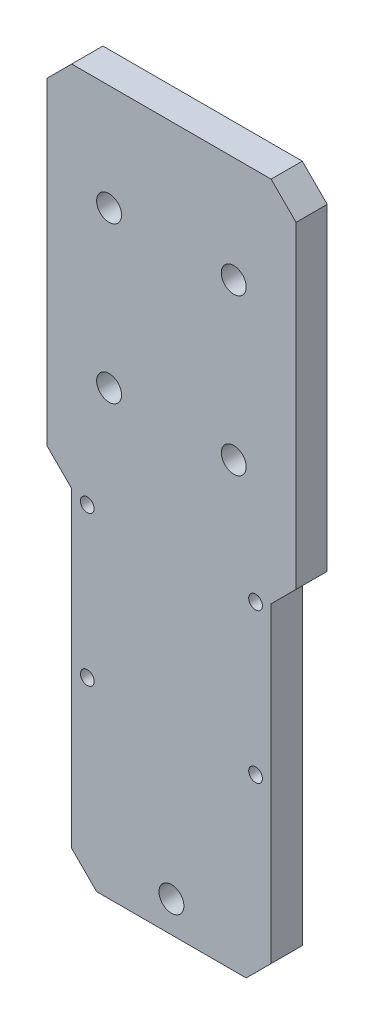
SolidWorks part; units mm, degrees
ref_plane "Alzado" through (0, 0, 0) normal (0, 0, 1) x (1, 0, 0)
ref_plane "Planta" through (0, 0, 0) normal (0, 1, 0) x (1, 0, 0)
ref_plane "Vista lateral" through (0, 0, 0) normal (1, 0, 0) x (0, 0, -1)
sketch "Croquis1" plane through (0, 0, 0) normal (0, 0, 1) x (1, 0, 0)
  line L0 (0, -27.5) -> (0, -61.5) construction
  line L1 (-20, 27.5) -> (20, 27.5)
  line L2 (-20, 27.5) -> (-20, -27.5)
  line L3 (-20, -27.5) -> (20, -27.5)
  line L4 (20, 27.5) -> (20, -27.5)
  line L5 (-20, 27.5) -> (20, -27.5) construction
  line L6 (-20, -27.5) -> (20, 27.5) construction
  line L7 (0, -32.5) -> (-13.5, -32.5) construction
  line L8 (16, -61.5) -> (-16, -61.5)
  line L9 (0, -61.5) -> (0, -27.5)
  line L10 (16, -27.5) -> (-16, -27.5)
  line L11 (-16, -61.5) -> (-16, -27.5)
  line L12 (-20, -27.5) -> (-16, -31.5)
  line L13 (20, -27.5) -> (16, -31.5)
  line L14 (16, -61.5) -> (16, -27.5)
  circle A0 centre (-13.5, -32.5) radius 1.1
  circle A3 centre (-13.5, -56.5) radius 1.1
  circle A4 centre (13.5, -32.5) radius 1.1
  circle A7 centre (13.5, -56.5) radius 1.1
  circle A8 centre (-13.5, -40.5) radius 1.1 [skipped]
  circle A9 centre (-13.5, -48.5) radius 1.1 [skipped]
  point P0 (0, 0)
  dimension "D5" = 2.2
  dimension "D1" = 40
  dimension "D2" = 55
  dimension "D3" = 16
  dimension "D4" = 13.5
  dimension "D7" = 34
  dimension "D8" = 5
  dimension "D9" = 45
  dimension "D6" = 4
extrude "FormaBase" add sketch "Croquis1" along normal blind 5
sketch "Croquis2" plane through (0, 0, 5) normal (0, 0, 1) x (1, 0, 0)
  line L0 (-20, 27.5) -> (-20, 23.4978)
  line L1 (-20, 27.5) -> (-20, -27.5) construction
  line L2 (-20, 23.4978) -> (-15.9978, 27.5)
  line L3 (-20, 27.5) -> (20, 27.5) construction
  line L4 (-15.9978, 27.5) -> (-20, 27.5)
  line L5 (0, 0) -> (0, 27.5) construction
  line L6 (20, 23.4978) -> (15.9978, 27.5)
  line L7 (20, 27.5) -> (20, 23.4978)
  line L8 (15.9978, 27.5) -> (20, 27.5)
  dimension "D1" = 45
  dimension "D2" = 5.66
extrude "Esquinas" cut sketch "Croquis2" against normal through all
sketch "Croquis3" plane through (0, 0, 5) normal (0, 0, 1) x (1, 0, 0)
  line L0 (-17.9989, 25.4989) -> (18, -29.5) construction
  line L1 (0, -2.75) -> (0, 2.75) construction
  line L2 (-20, 23.4978) -> (-15.9978, 27.5) construction
  line L3 (20, -27.5) -> (16, -31.5) construction
  line L4 (-9.9994, 10.4994) -> (10.0006, 10.4994)
  line L5 (-9.9994, 10.4994) -> (-9.9994, -14.5006)
  line L6 (-9.9994, -14.5006) -> (10.0006, -14.5006)
  line L7 (10.0006, 10.4994) -> (10.0006, -14.5006)
  line L8 (-9.9994, 10.4994) -> (10.0006, -14.5006) construction
  line L9 (-9.9994, -14.5006) -> (10.0006, 10.4994) construction
  circle A0 centre (10.0006, 10.4994) radius 2
  circle A1 centre (10.0006, -14.5006) radius 2
  circle A2 centre (-10.0006, 10.4994) radius 2
  circle A3 centre (-10.0006, -14.5006) radius 2
  point P2 (0.0006, -2.0006)
  dimension "D1" = 25
extrude "BarrenosEjeZ" cut sketch "Croquis3" against normal through all contours A2 | A0 | A1 | A3
sketch "Croquis4" plane through (0, 0, 5) normal (0, 0, 1) x (1, 0, 0)
  line L0 (-16, -81.4978) -> (-11.9978, -85.5)
  line L1 (-16, -61.5) -> (16, -61.5)
  line L2 (-16, -61.5) -> (-16, -85.5)
  line L3 (-16, -85.5) -> (16, -85.5)
  line L4 (16, -61.5) -> (16, -85.5)
  line L6 (0, -85.5) -> (0, -61.5) construction
  line L7 (16, -81.4978) -> (11.9978, -85.5)
  line M14 (-16, -61.5) -> (16, -61.5)
  dimension "D1" = 24
  dimension "D2" = 45
  dimension "D3" = 5.66
extrude "Saliente-Extruir2" add sketch "Croquis4" against normal through all contours L3 L6 L2 L0 M14 | L6 L3 L7 L4 L1
sketch "Croquis5" plane through (0, 0, 5) normal (0, 0, 1) x (1, 0, 0)
  line L0 (0, -85.5) -> (0, -80.5) construction
  line L1 (-11.9978, -85.5) -> (11.9978, -85.5) construction
  circle A2 centre (0, -80.5) radius 2
  dimension "D1" = 5
extrude "Cortar-Extruir9" cut sketch "Croquis5" against normal through all
